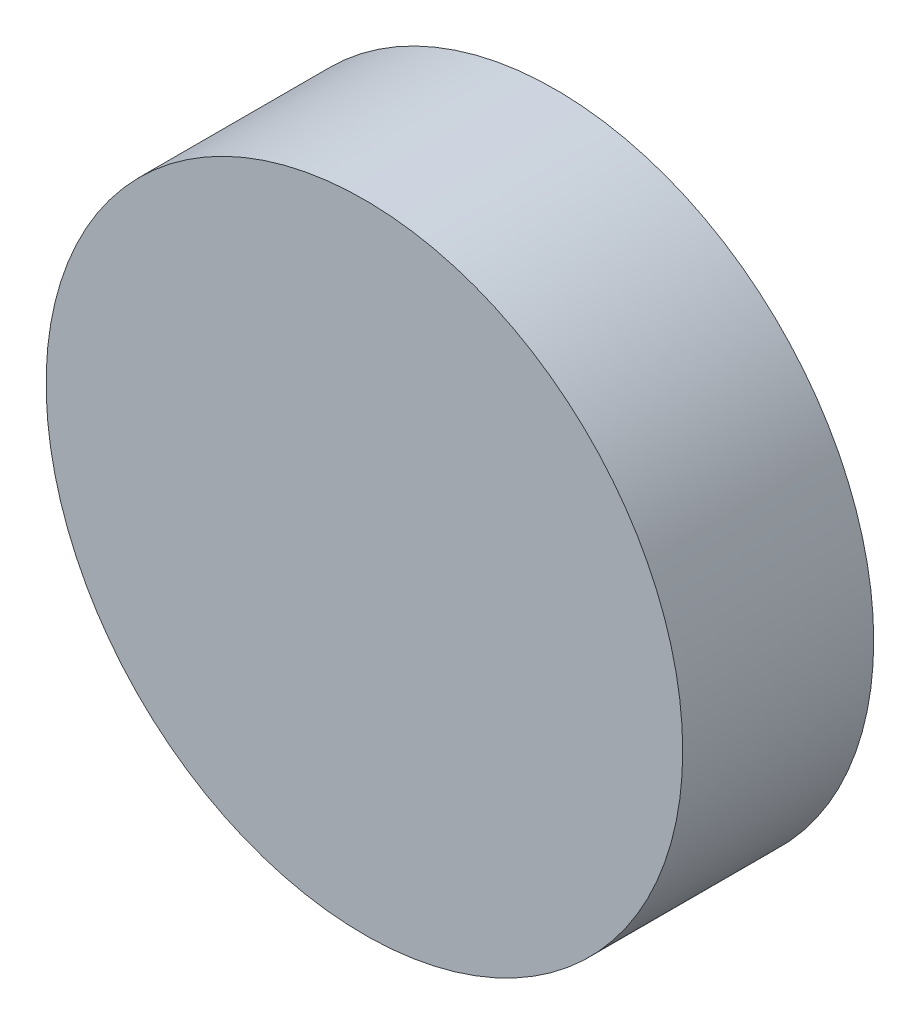
SolidWorks part; units mm, degrees
ref_plane "前视基准面" through (0, 0, 0) normal (0, 0, 1) x (1, 0, 0)
ref_plane "上视基准面" through (0, 0, 0) normal (0, 1, 0) x (1, 0, 0)
ref_plane "右视基准面" through (0, 0, 0) normal (1, 0, 0) x (0, 0, -1)
sketch "草图1" plane through (0, 0, 0) normal (0, 0, 1) x (1, 0, 0)
  circle A0 centre (0, 0) radius 25
  dimension "D1" = 50
extrude "凸台-拉伸1" add sketch "草图1" along normal mid plane 15
